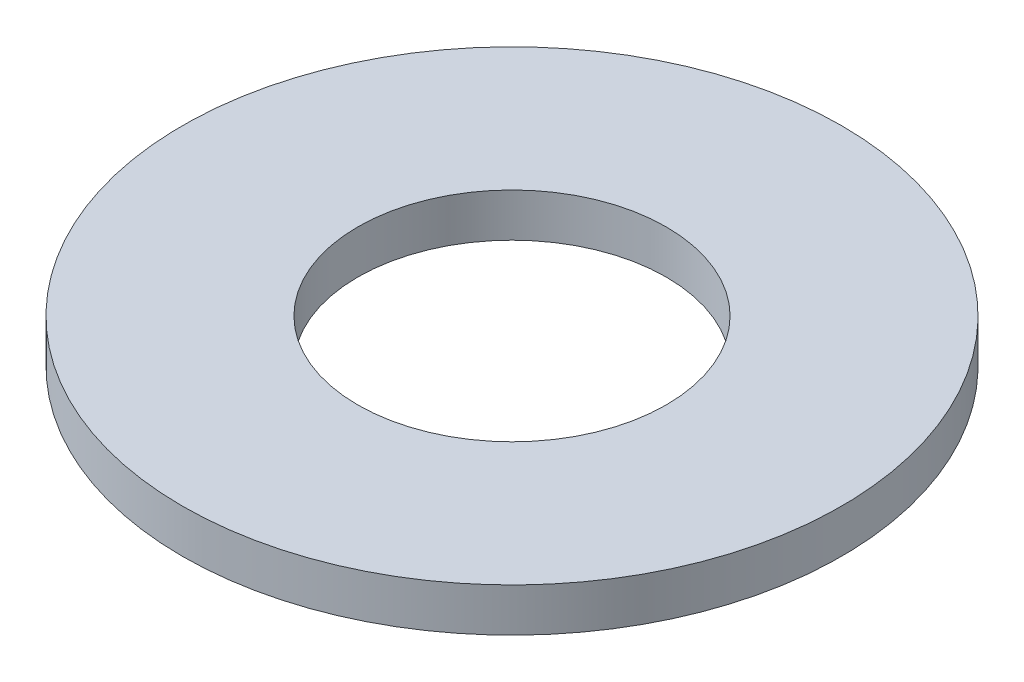
SolidWorks part; units mm, degrees
ref_plane "Front Plane" through (0, 0, 0) normal (0, 0, 1) x (1, 0, 0)
ref_plane "Top Plane" through (0, 0, 0) normal (0, 1, 0) x (1, 0, 0)
ref_plane "Right Plane" through (0, 0, 0) normal (1, 0, 0) x (0, 0, -1)
sketch "Sketch1" plane through (0, 0, 0) normal (0, 1, 0) x (1, 0, 0)
  circle A0 centre (0, 0) radius 6.35
  dimension "OD" = 12.7
extrude "Boss-Extrude1" add sketch "Sketch1" along normal blind 0.8382
sketch "Sketch5" plane through (0, 0.8382, 0) normal (0, 1, 0) x (-1, 0, 0)
  circle A0 centre (0, 0) radius 2.9718
  dimension "ID" = 5.9436
extrude "Cut-Extrude1" cut sketch "Sketch5" against normal through all
